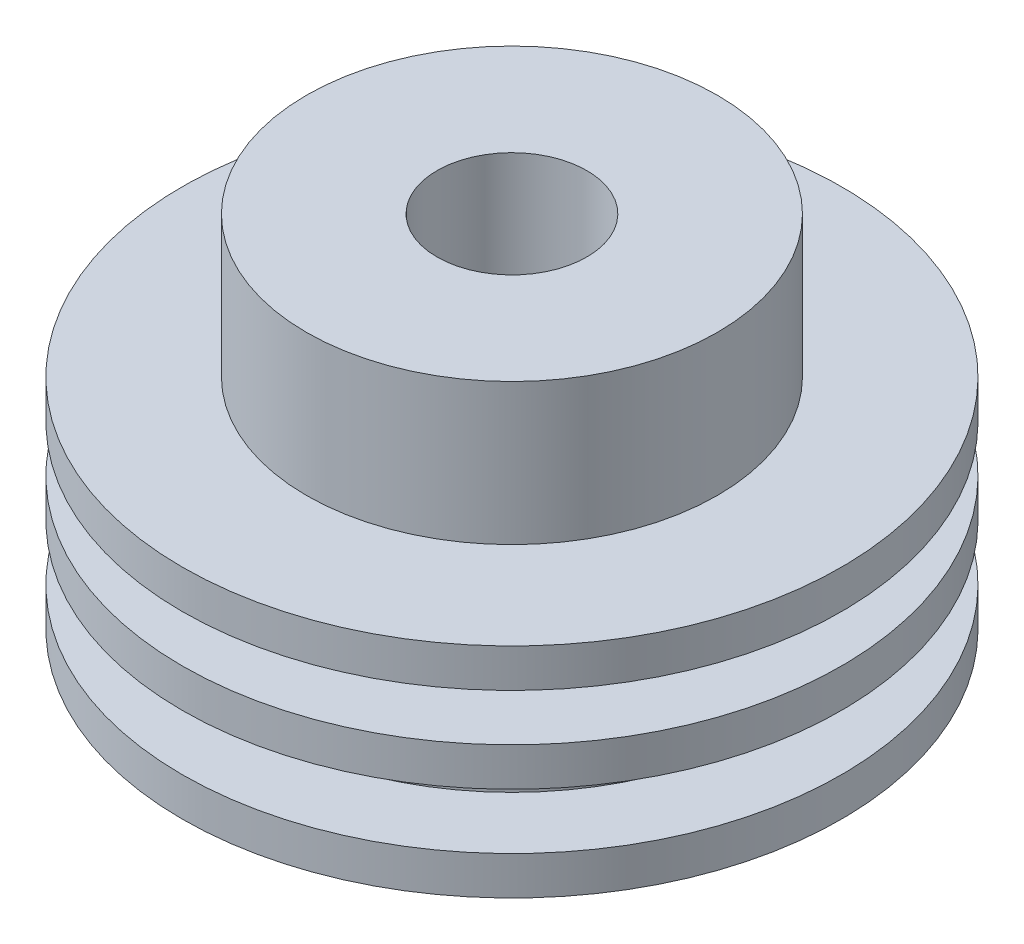
SolidWorks part; units mm, degrees
ref_plane "前视基准面" through (0, 0, 0) normal (0, 0, 1) x (1, 0, 0)
ref_plane "上视基准面" through (0, 0, 0) normal (0, 1, 0) x (1, 0, 0)
ref_plane "右视基准面" through (0, 0, 0) normal (1, 0, 0) x (0, 0, -1)
sketch "草图1" plane through (0, 0, 0) normal (0, 0, 1) x (1, 0, 0)
  line L0 (0, 82.972) -> (0, 0) construction
  line L1 (6.3476, 61.7529) -> (17.4105, 61.7529)
  line L2 (17.4105, 61.7529) -> (17.4105, 49.7832)
  line L3 (17.4105, 49.7832) -> (27.9294, 49.7832)
  line L4 (27.9294, 49.7832) -> (27.9294, 46.5187)
  line L5 (27.9294, 46.5187) -> (21.5818, 46.5187)
  line L6 (21.5818, 46.5187) -> (21.5818, 42.5288)
  line L7 (21.5818, 42.5288) -> (27.9294, 42.5288)
  line L8 (27.9294, 42.5288) -> (27.9294, 39.2643)
  line L9 (27.9294, 39.2643) -> (21.5818, 39.2643)
  line L10 (21.5818, 39.2643) -> (21.5818, 34.549)
  line L11 (21.5818, 34.549) -> (27.9294, 34.549)
  line L12 (27.9294, 34.549) -> (27.9294, 31.2845)
  line L13 (27.9294, 31.2845) -> (6.3476, 31.2845)
  line L14 (6.3476, 61.7529) -> (6.3476, 31.2845)
revolve "旋转1" add sketch "草图1" angle 360 about L0
